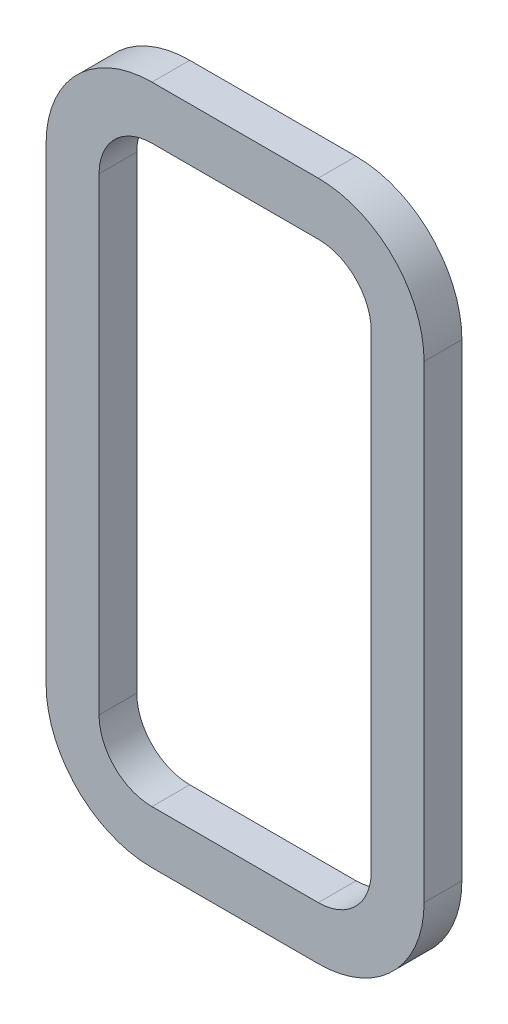
SolidWorks part; units mm, degrees
material "普通碳钢"
ref_plane "前视基准面" through (0, 0, 0) normal (0, 0, 1) x (1, 0, 0)
ref_plane "上视基准面" through (0, 0, 0) normal (0, 1, 0) x (1, 0, 0)
ref_plane "右视基准面" through (0, 0, 0) normal (1, 0, 0) x (0, 0, -1)
sketch "草图1" plane through (0, 0, 0) normal (0, 0, 1) x (1, 0, 0)
  line L0 (0, 0) -> (15.3811, 0) construction
  line L1 (-50, 90) -> (50, 90)
  line L2 (-50, 90) -> (-50, -90)
  line L3 (-50, -90) -> (50, -90)
  line L4 (50, 90) -> (50, -90)
  line L5 (-36, 76) -> (36, 76)
  line L6 (-36, 76) -> (-36, -76)
  line L7 (-36, -76) -> (36, -76)
  line L8 (36, 76) -> (36, -76)
  line L9 (0, 0) -> (0, 19.6754) construction
  point P13 (0, 0)
  dimension "D1" = 180
  dimension "D3" = 14
  dimension "D2" = 100
  dimension "D4" = 14
extrude "凸台-拉伸1" add sketch "草图1" along normal blind 10
fillet "圆角1" radius 14 4 edges at (-36, -76, 5) (-36, 76, 5) (36, 76, 5) (36, -76, 5)
fillet "圆角2" radius 28 4 edges at (-50, -90, 5) (50, -90, 5) (-50, 90, 5) (50, 90, 5)
